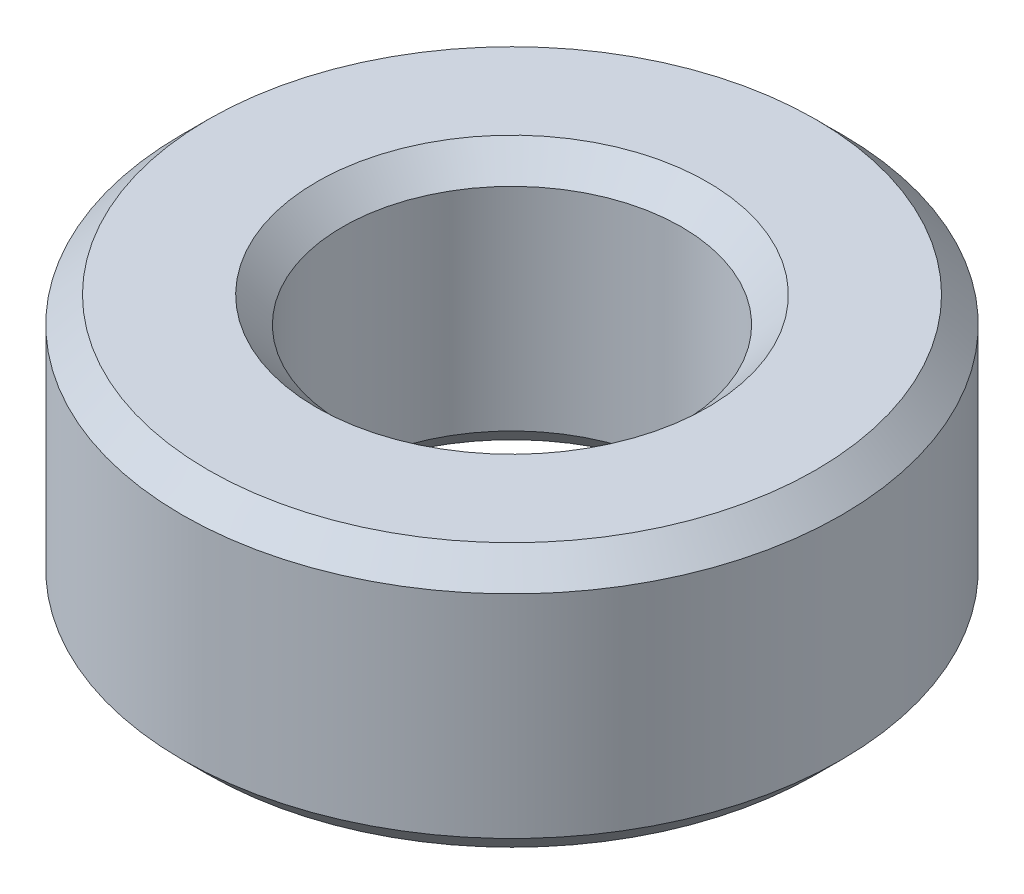
SolidWorks part; units mm, degrees
ref_plane "Front Plane" through (0, 0, 0) normal (0, 0, 1) x (1, 0, 0)
ref_plane "Top Plane" through (0, 0, 0) normal (0, 1, 0) x (1, 0, 0)
ref_plane "Right Plane" through (0, 0, 0) normal (1, 0, 0) x (0, 0, -1)
sketch "Sketch1" plane through (0, 0, 0) normal (0, 1, 0) x (1, 0, 0)
  circle A0 centre (0, 0) radius 6.35
extrude "Boss-Extrude1" add sketch "Sketch1" along normal blind 5.08
hole_wizard "F (0.257) Diameter Hole1" positions "Sketch3" profile "Sketch2" hole size "F" standard "ANSI Inch" end condition through all
sketch "Sketch3" plane through (0, 5.08, 0) normal (0, 1, 0) x (1, 0, 0)
  point P0 (0, 0)
sketch "Sketch2" plane through (0, 5.08, 0) normal (1, 0, 0) x (0, 0, 1)
  line L0 (0, 0) -> (0, 5.08)
  line L1 (0, 5.08) -> (3.2639, 5.08)
  line L2 (3.2639, 5.08) -> (3.2639, 0)
  line L5 (3.2639, 0) -> (0, 0)
  line L11 (0, -6.35) -> (0, 107.95) construction
  dimension "Thru Hole Dia." = 6.5278
  dimension "Thru Hole Depth" = 5.08
chamfer "Chamfer1" distance 0.5 angle 45 4 edges at (0, 0, 6.35) (0, 0, 3.2639) (0, 5.08, 6.35) (0, 5.08, 3.2639)
